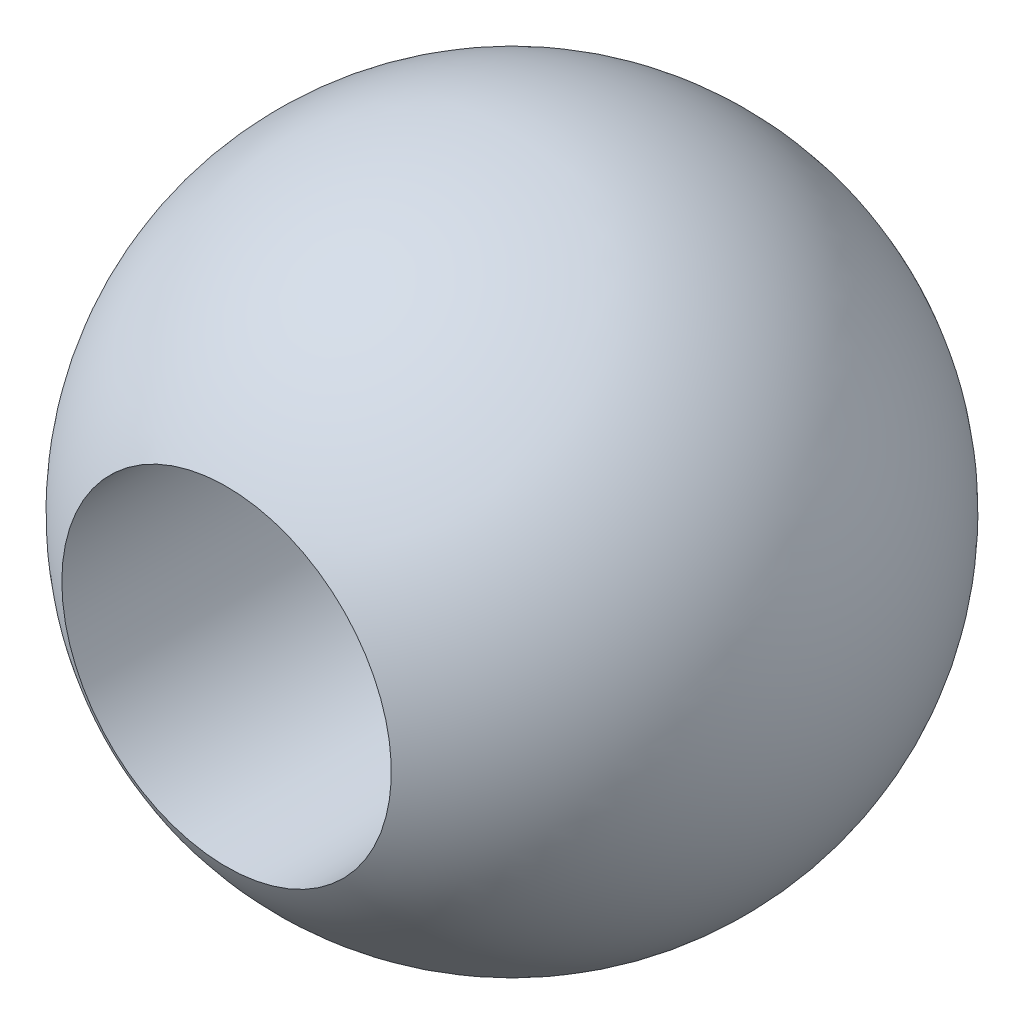
SolidWorks part; units mm, degrees
ref_plane "前视基准面" through (0, 0, 0) normal (0, 0, 1) x (1, 0, 0)
ref_plane "上视基准面" through (0, 0, 0) normal (0, 1, 0) x (1, 0, 0)
ref_plane "右视基准面" through (0, 0, 0) normal (1, 0, 0) x (0, 0, -1)
other "Configuration Table"
sketch "草图1" plane through (0, 0, 0) normal (0, 0, 1) x (1, 0, 0)
  line L0 (0, 4) -> (0, -4)
  arc A1 (0, -4) -> (0, 4) centre (0, 0) ccw
  dimension "D1" = 4
  dimension "D2" = 8
revolve "旋转1" add sketch "草图1" angle 360 about L0
sketch "草图2" plane through (0, 0, 0) normal (0, 0, 1) x (1, 0, 0)
  circle A0 centre (0, 0) radius 2
  dimension "D1" = 4
extrude "切除-拉伸1" cut sketch "草图2" against normal through all both and the other way through all
ref_plane "基准面1" through (0, 0, -3.4641) normal (0, 0, 1) x (1, 0, 0)
ref_plane "基准面2" through (0, 0, 3.4641) normal (0, 0, 1) x (1, 0, 0)
